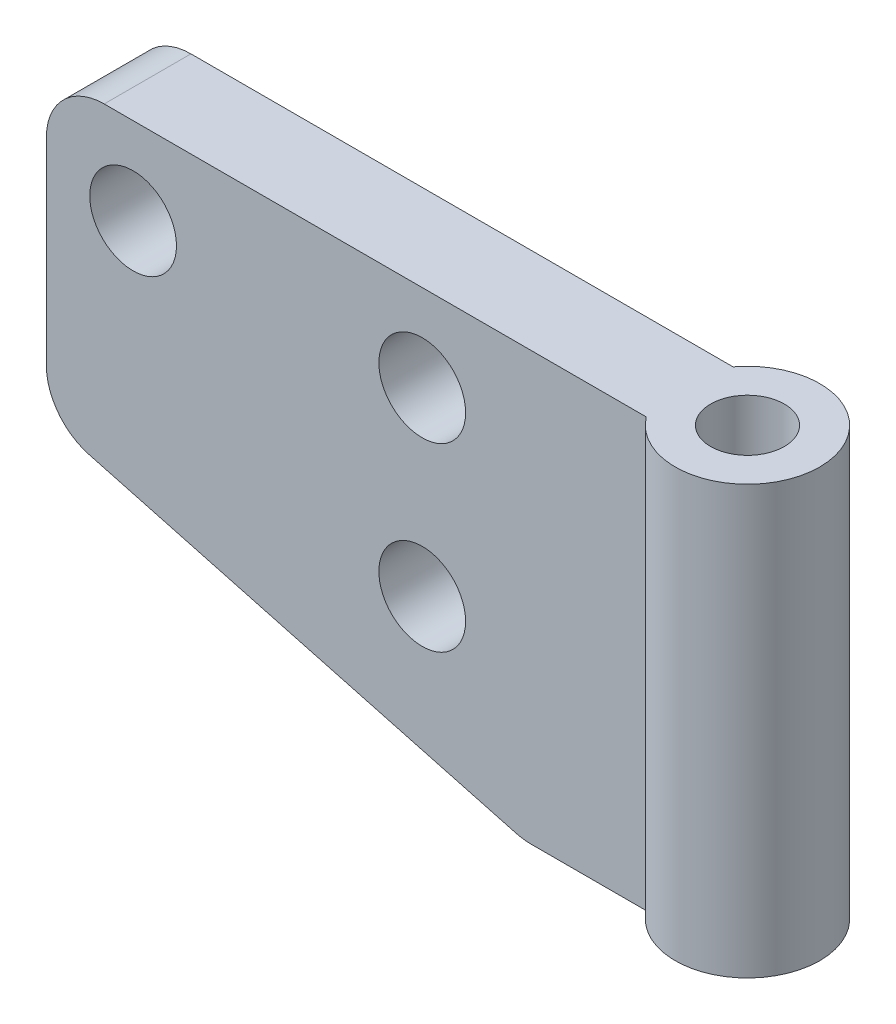
SolidWorks part; units mm, degrees
ref_plane "前视基准面" through (0, 0, 0) normal (0, 0, 1) x (1, 0, 0)
ref_plane "上视基准面" through (0, 0, 0) normal (0, 1, 0) x (1, 0, 0)
ref_plane "右视基准面" through (0, 0, 0) normal (1, 0, 0) x (0, 0, -1)
other "Configuration Table"
sketch "草图2" plane through (0, 0, 0) normal (0, 0, 1) x (1, 0, 0)
  line L0 (0, 0) -> (20, 0) construction
  line L1 (20, 0) -> (20, -12.5) construction
  line L2 (0, 0) -> (-6, 0) construction
  line L3 (-6, 0) -> (-6, 6) construction
  line L4 (20, -12.5) -> (20, -23.58) construction
  line L5 (20, -23.58) -> (27, -23.58) construction
  line L6 (27, -23.58) -> (39.5, -23.58) construction
  line L7 (26.4913, -23.4437) -> (-3.0353, -15.5321)
  line L8 (-2, 6) -> (39.5, 6)
  line L9 (-6, 6) -> (-6, -23.58) construction
  line L10 (-6, -23.58) -> (39.5, -23.58) construction
  line L11 (39.5, 6) -> (39.5, -23.58)
  line L12 (-6, -11.6684) -> (-6, 2)
  line L13 (27.5266, -23.58) -> (39.5, -23.58)
  circle A0 centre (0, 0) radius 3
  circle A1 centre (20, 0) radius 3
  circle A2 centre (20, -12.5) radius 3
  arc A3 (26.4913, -23.4437) -> (27.5266, -23.58) centre (27.5266, -19.58) ccw
  arc A4 (-3.0353, -15.5321) -> (-6, -11.6684) centre (-2, -11.6684) cw
  arc A5 (-2, 6) -> (-6, 2) centre (-2, 2) ccw
  point P20 (-6, -14.7377)
  dimension "D1" = 6
  dimension "D3" = 6
  dimension "D5" = 6
  dimension "D12" = 4
  dimension "D2" = 20
  dimension "D4" = 12.5
  dimension "D6" = 6
  dimension "D7" = 6
  dimension "D8" = 11.08
  dimension "D9" = 7
  dimension "D10" = 12.5
  dimension "D11" = 15
  dimension "D13" = 29.58
extrude "凸台-拉伸1" add sketch "草图2" along normal blind 6
sketch "草图3" plane through (0, 6, 0) normal (0, 1, 0) x (1, 0, 0)
  line L0 (39.5, -6) -> (39.5, 0) construction
  circle A0 centre (39.5, -3) radius 5
  dimension "D1" = 10
extrude "凸台-拉伸2" add sketch "草图3" against normal through all contours A0
sketch "草图4" plane through (0, 6, 0) normal (0, 1, 0) x (1, 0, 0)
  circle A0 centre (39.5, -3) radius 2.55
  dimension "D1" = 5.1
extrude "切除-拉伸1" cut sketch "草图4" against normal through all
